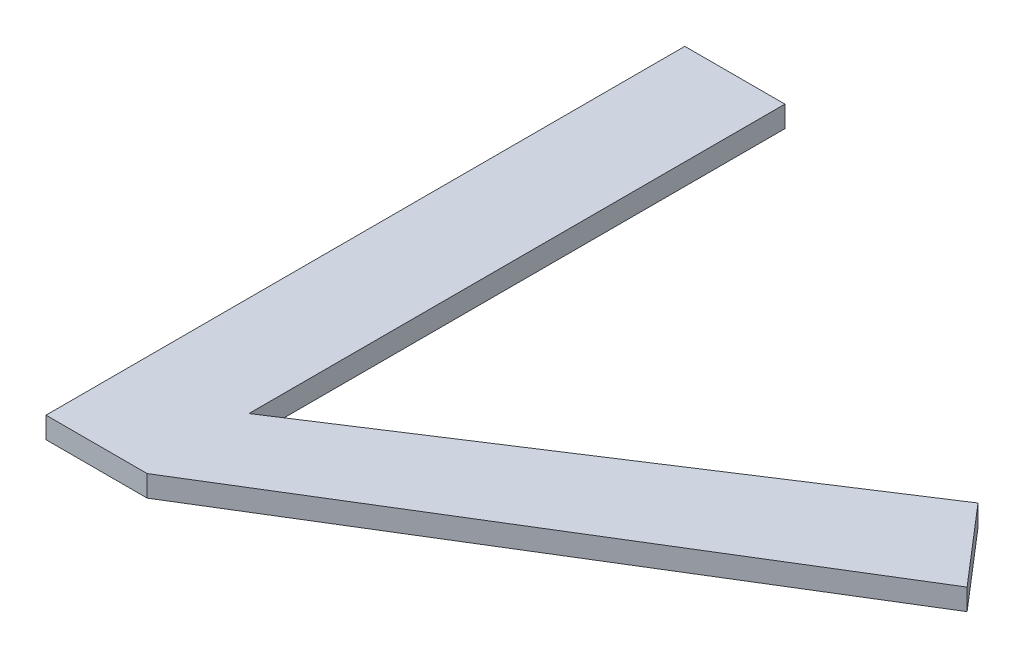
SolidWorks part; units mm, degrees
ref_plane "Front Plane" through (0, 0, 0) normal (0, 0, 1) x (1, 0, 0)
ref_plane "Top Plane" through (0, 0, 0) normal (0, 1, 0) x (1, 0, 0)
ref_plane "Right Plane" through (0, 0, 0) normal (1, 0, 0) x (0, 0, -1)
sketch "Sketch1" plane through (0, 0, 0) normal (0, 1, 0) x (1, 0, 0)
  line L0 (0, 0) -> (0, 25.1687)
  line L1 (0, 25.1687) -> (-4.7, 25.1687)
  line L2 (-4.7, 25.1687) -> (-4.7, -4.8313)
  line L3 (-4.7, -4.8313) -> (0.05, -4.8313)
  line L4 (0.05, -4.8313) -> (23.9208, 9.8037)
  line L5 (23.9208, 9.8037) -> (20.7571, 13.4798)
  line L6 (20.7571, 13.4798) -> (0, 0)
  point P5 (24.5021, 10.398)
  point P9 (0, 0)
  point P10 (-0.45, -2.8804)
  point P11 (0, 0)
  point P12 (0, -2.8804)
  point P13 (0, -2.8804)
  point P14 (0, -2.8804)
  point P15 (24.3563, 10.2289)
  point P16 (0, -4.0715)
  point P17 (0, -4.8313)
  dimension "D1" = 57
  dimension "D2" = 30
  dimension "D3" = 4.7
  dimension "D4" = 24.75
  dimension "D5" = 4.85
  dimension "D6" = 28
  dimension "D7" = 4.75
extrude "Boss-Extrude1" add sketch "Sketch1" along normal blind 1
